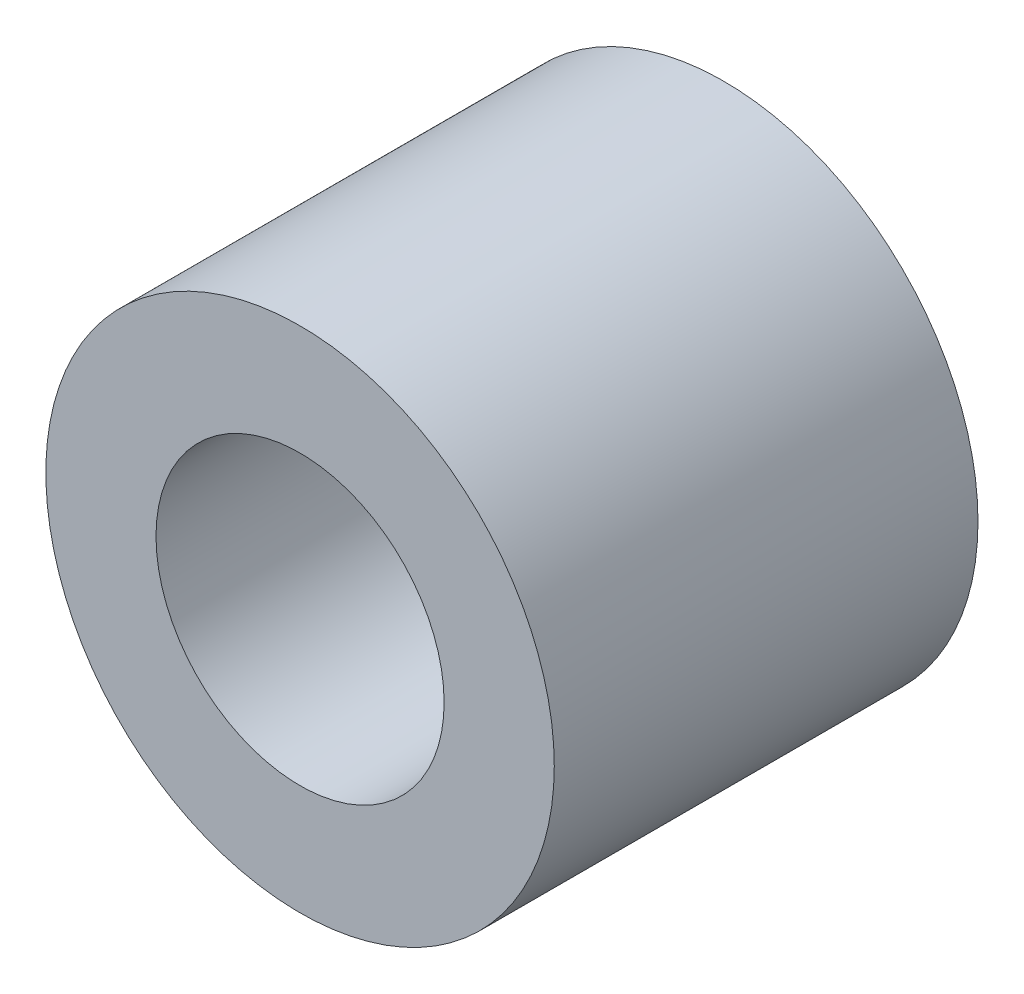
SolidWorks part; units mm, degrees
ref_plane "Front Plane" through (0, 0, 0) normal (1, 0, 0) x (0, 1, 0)
ref_plane "Top Plane" through (0, 0, 0) normal (0, 0, 1) x (0, 1, 0)
ref_plane "Right Plane" through (0, 0, 0) normal (0, 1, 0) x (-1, 0, 0)
sketch "Sketch2" plane through (0, 0, 0) normal (0, 0, 1) x (0, 1, 0)
  circle A0 centre (0, 0) radius 3
  dimension "D1" = 6
extrude "Boss-Extrude1" add sketch "Sketch2" along normal blind 5
sketch "Sketch3" plane through (0, 0, 5) normal (0, 0, 1) x (1, 0, 0)
  circle A0 centre (0, 0) radius 1.7
  dimension "D1" = 3.4
extrude "Cut-Extrude1" cut sketch "Sketch3" against normal through all
